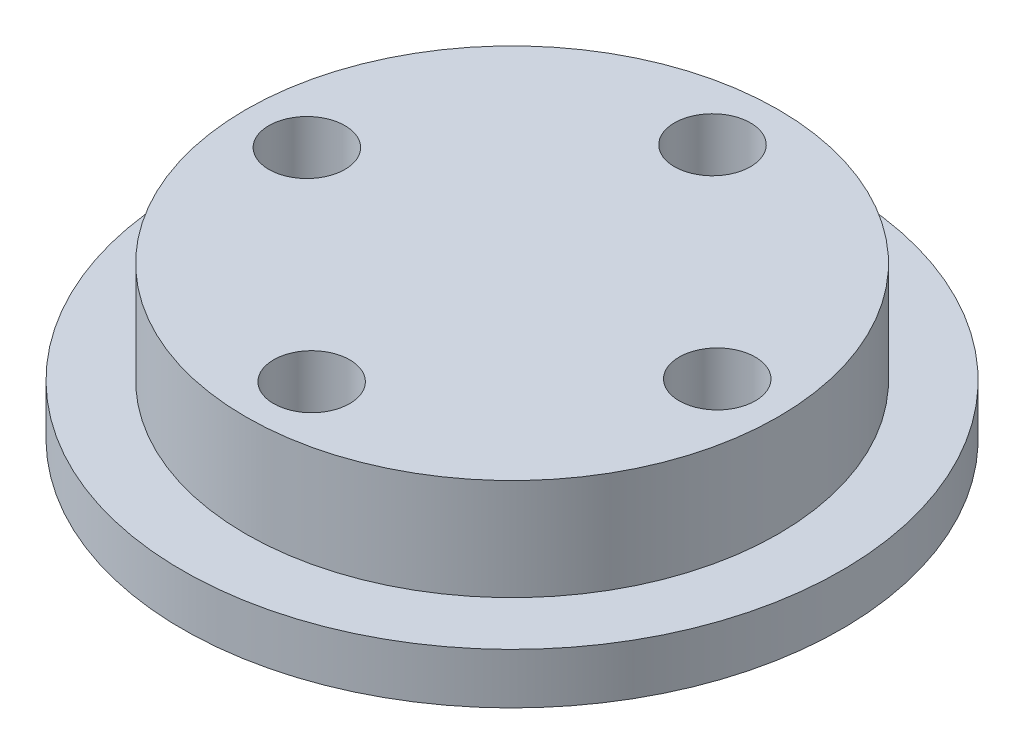
SolidWorks part; units mm, degrees
ref_plane "Plan de face" through (0, 0, 0) normal (0, 0, 1) x (1, 0, 0)
ref_plane "Plan de dessus" through (0, 0, 0) normal (0, 1, 0) x (1, 0, 0)
ref_plane "Plan de droite" through (0, 0, 0) normal (1, 0, 0) x (0, 0, -1)
sketch "Esquisse1" plane through (0, 0, 0) normal (0, 1, 0) x (1, 0, 0)
  circle A0 centre (0, 0) radius 10.5
  point P15 (0, 0)
  dimension "D4" = 21
extrude "Boss.-Extru.1" add sketch "Esquisse1" along normal blind 4
sketch "Esquisse2" plane through (0, 0, 0) normal (0, -1, 0) x (1, 0, 0)
  circle A0 centre (0, 0) radius 13
  dimension "D1" = 26
extrude "Boss.-Extru.2" add sketch "Esquisse2" along normal blind 2
sketch "Esquisse3" plane through (0, 4, 0) normal (0, 1, 0) x (1, 0, 0)
  circle A0 centre (-7.9994, -0.094) radius 1.5
  circle A1 centre (-0.094, 7.9994) radius 1.5
  circle A2 centre (0.094, -7.9994) radius 1.5
  circle A3 centre (7.9994, 0.094) radius 1.5
extrude "Enlèv. mat.-Extru.1" cut sketch "Esquisse3" against normal through all
